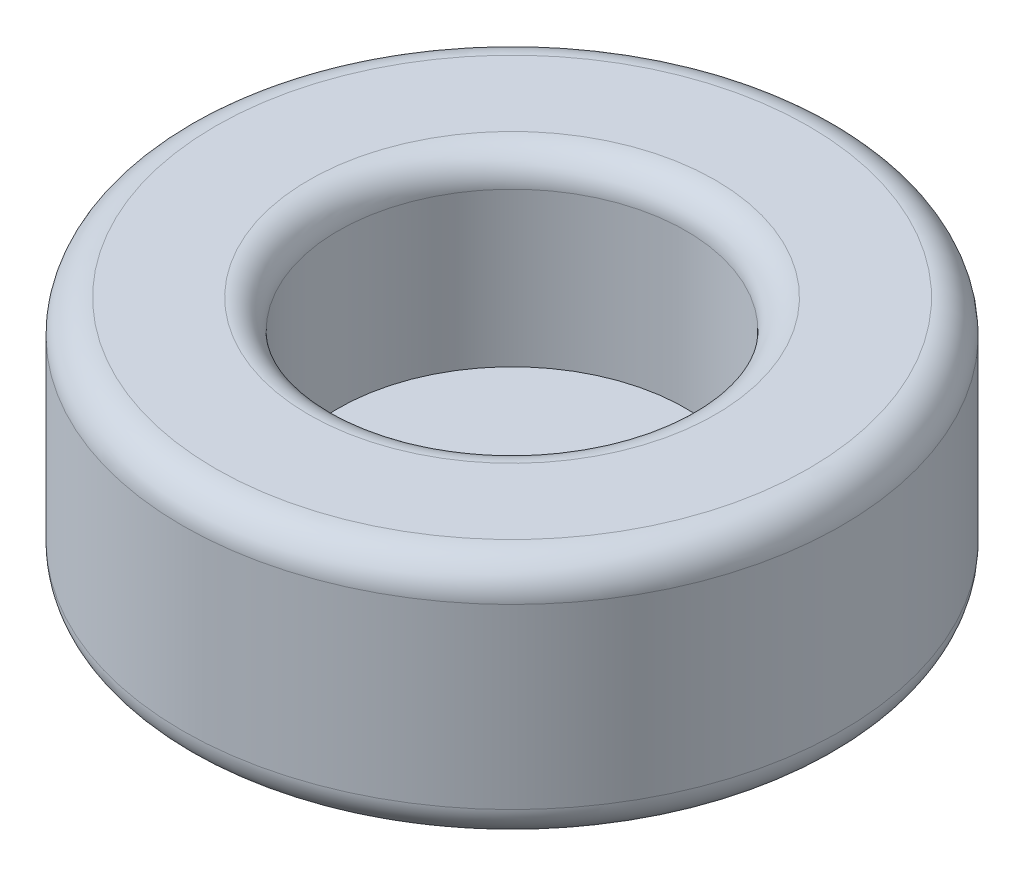
SolidWorks part; units mm, degrees
ref_plane "Front Plane" through (0, 0, 0) normal (0, 0, 1) x (1, 0, 0)
ref_plane "Top Plane" through (0, 0, 0) normal (0, 1, 0) x (1, 0, 0)
ref_plane "Right Plane" through (0, 0, 0) normal (1, 0, 0) x (0, 0, -1)
sketch "Sketch1" plane through (0, 0, 0) normal (0, 1, 0) x (1, 0, 0)
  circle A0 centre (0, 0) radius 228.6
  dimension "D1" = 457.2
extrude "Boss-Extrude1" add sketch "Sketch1" along normal blind 168.91
fillet "Fillet1" radius 22.86 2 edges at (0, 168.91, 228.6) (0, 0, 228.6)
sketch "Sketch2" plane through (0, 168.91, 0) normal (0, 1, 0) x (1, 0, 0)
  circle A0 centre (0, 0) radius 120.65
  dimension "D1" = 241.3
extrude "Cut-Extrude1" cut sketch "Sketch2" against normal blind 127
fillet "Fillet2" radius 20.32 1 edges at (0, 168.91, 120.65)
